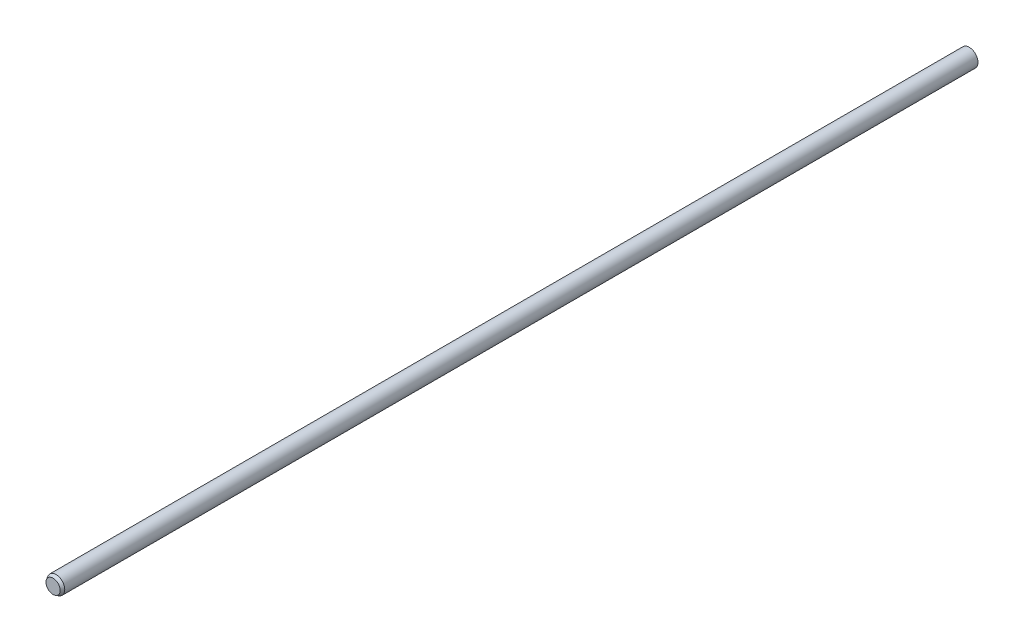
SolidWorks part; units mm, degrees
material "1060 Alloy"
ref_plane "Front Plane" through (0, 0, 0) normal (0, 0, 1) x (1, 0, 0)
ref_plane "Top Plane" through (0, 0, 0) normal (0, 1, 0) x (1, 0, 0)
ref_plane "Right Plane" through (0, 0, 0) normal (1, 0, 0) x (0, 0, -1)
sketch "Sketch1" plane through (0, 0, 0) normal (0, 0, 1) x (1, 0, 0)
  circle A0 centre (0, 0) radius 3
extrude "Boss-Extrude1" add sketch "Sketch1" along normal blind 314
chamfer "Chamfer1" distance 1 angle 30 2 edges at (3, 0, 314) (3, 0, 0)
